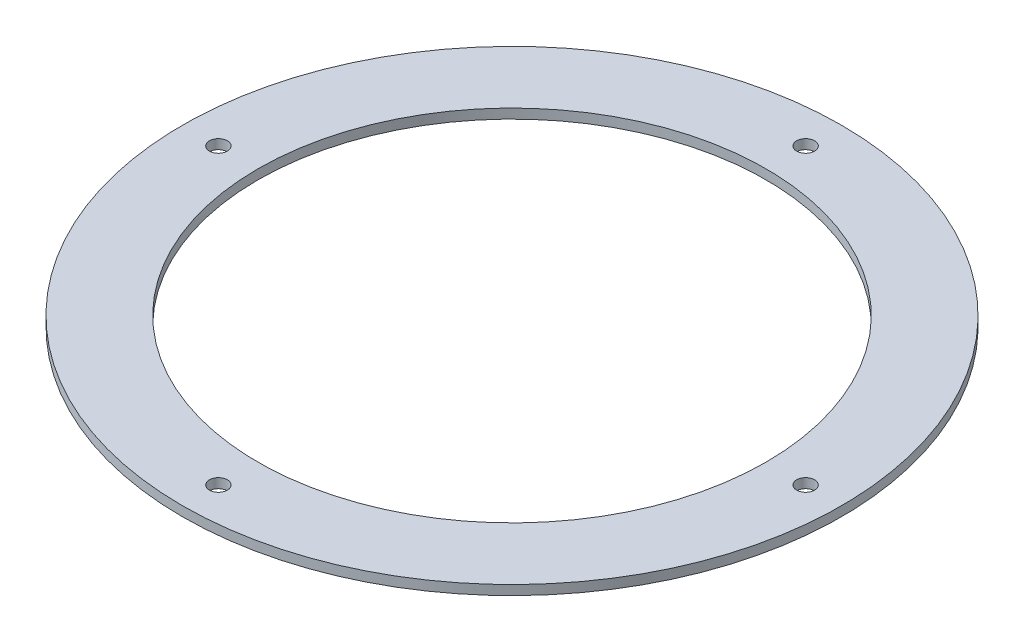
SolidWorks part; units mm, degrees
material "6063-T4"
ref_plane "前视基准面" through (0, 0, 0) normal (0, 0, 1) x (1, 0, 0)
ref_plane "上视基准面" through (0, 0, 0) normal (0, 1, 0) x (1, 0, 0)
ref_plane "右视基准面" through (0, 0, 0) normal (1, 0, 0) x (0, 0, -1)
sketch "草图1" plane through (0, 0, 0) normal (0, 1, 0) x (1, 0, 0)
  circle A0 centre (0, 0) radius 55
  dimension "D1" = 110
extrude "拉伸-薄壁1" add sketch "草图1" along normal blind 1.6 thin thin type one direction reverse wall 12.6
sketch "草图2" plane through (0, 1.6, 0) normal (0, 1, 0) x (1, 0, 0)
  line L0 (-55, 0) -> (55, 0) construction
  line L1 (0, 55) -> (0, -55) construction
  circle A0 centre (0, 0) radius 55 construction
  circle A1 centre (-49, 0) radius 1.5
  circle A2 centre (0, 49) radius 1.5
  circle A3 centre (49, 0) radius 1.5
  circle A4 centre (0, -49) radius 1.5
  point P7 (-49, 0)
  point P8 (0, 49)
  dimension "D3" = 3
  dimension "D4" = 3
  dimension "D1" = 6
  dimension "D2" = 6
extrude "切除-拉伸1" cut sketch "草图2" against normal up to surface (1.6 mm away) up to face at (0, 0, 55)
sketch "草图3" plane through (0, 1.6, 0) normal (0, 1, 0) x (1, 0, 0)
  circle A0 centre (-49, 0) radius 2.7558
